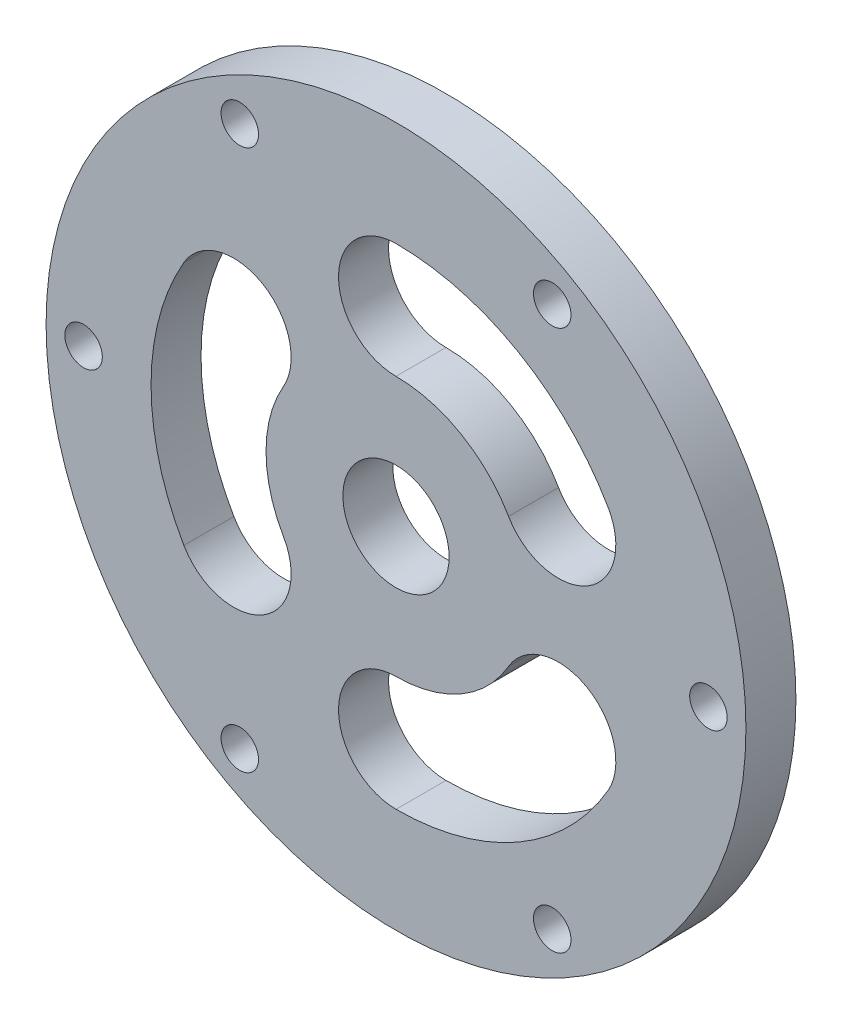
SolidWorks part; units mm, degrees
ref_plane "前视基准面" through (0, 0, 0) normal (0, 0, 1) x (1, 0, 0)
ref_plane "上视基准面" through (0, 0, 0) normal (0, 1, 0) x (1, 0, 0)
ref_plane "右视基准面" through (0, 0, 0) normal (1, 0, 0) x (0, 0, -1)
sketch "草图1" plane through (0, 0, 0) normal (0, 0, 1) x (1, 0, 0)
  line L0 (0, 0) -> (0, -3.3498) construction
  line L1 (12.9904, -7.5) -> (0, 0) construction
  line L2 (-12.9904, -7.5) -> (0, -15) construction
  line L3 (-6.4952, -11.25) -> (0, 0) construction
  line L4 (0, 0) -> (14, 24.2487) construction
  line L5 (14, 24.2487) -> (12.5, 21.6506) construction
  circle A0 centre (0, 0) radius 15 construction
  circle A11 centre (0, 0) radius 4.25
  arc A17 (9.0067, -5.2) -> (16.9741, -9.8) centre (12.9904, -7.5) cw
  arc A18 (0, -10.4) -> (0, -19.6) centre (0, -15) ccw
  arc A19 (-9.0067, 5.2) -> (-9.0067, -5.2) centre (0, 0) ccw
  arc A20 (-16.9741, 9.8) -> (-16.9741, -9.8) centre (0, 0) ccw
  arc A21 (0, -10.4) -> (9.0067, -5.2) centre (0, 0) ccw
  arc A22 (0, -19.6) -> (16.9741, -9.8) centre (0, 0) ccw
  arc A23 (-9.0067, -5.2) -> (-16.9741, -9.8) centre (-12.9904, -7.5) cw
  arc A24 (-9.0067, 5.2) -> (-16.9741, 9.8) centre (-12.9904, 7.5) ccw
  arc A25 (9.0067, 5.2) -> (0, 10.4) centre (0, 0) ccw
  arc A26 (16.9741, 9.8) -> (0, 19.6) centre (0, 0) ccw
  arc A27 (0, 10.4) -> (0, 19.6) centre (0, 15) cw
  arc A28 (9.0067, 5.2) -> (16.9741, 9.8) centre (12.9904, 7.5) ccw
  circle A31 centre (0, 0) radius 35.5 construction
  circle A32 centre (0, 0) radius 25 construction
  circle A50 centre (0, 0) radius 28
  circle A54 centre (12.5, 21.6506) radius 1.5
  circle A55 centre (25, 0) radius 1.5
  circle A56 centre (12.5, -21.6506) radius 1.5
  circle A57 centre (-12.5, -21.6506) radius 1.5
  circle A58 centre (-25, 0) radius 1.5
  circle A59 centre (-12.5, 21.6506) radius 1.5
  dimension "D1" = 3
  dimension "D2" = 6
extrude "凸台-拉伸1" add sketch "草图1" along normal blind 4
